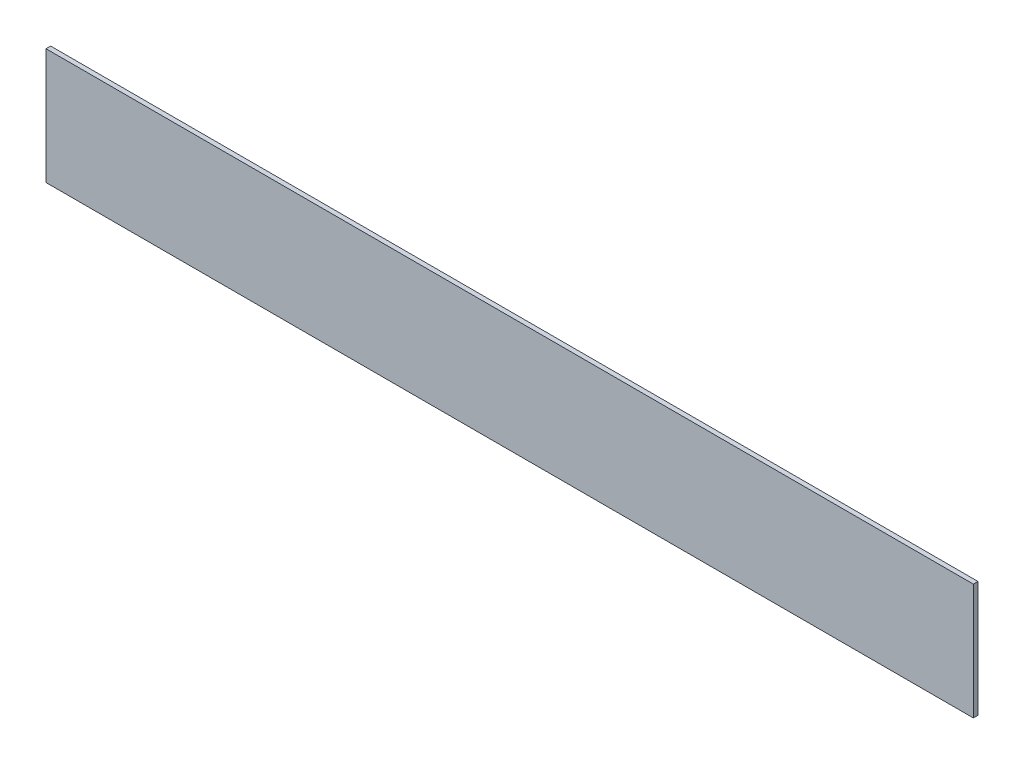
SolidWorks part; units mm, degrees
ref_plane "Front Plane" through (0, 0, 0) normal (0, 0, 1) x (1, 0, 0)
ref_plane "Top Plane" through (0, 0, 0) normal (0, 1, 0) x (1, 0, 0)
ref_plane "Right Plane" through (0, 0, 0) normal (1, 0, 0) x (0, 0, -1)
other "Configuration Table"
sketch "Sketch1" plane through (0, 0, 0) normal (0, 0, 1) x (1, 0, 0)
  line L1 (0, 1.6) -> (320, 1.6)
  line L2 (0, 1.6) -> (0, 41.6)
  line L3 (0, 41.6) -> (320, 41.6)
  line L4 (320, 1.6) -> (320, 41.6)
extrude "KUTU_duvar_arka_1" add sketch "Sketch1" against normal blind 1.6 from offset 318.4 separate body
